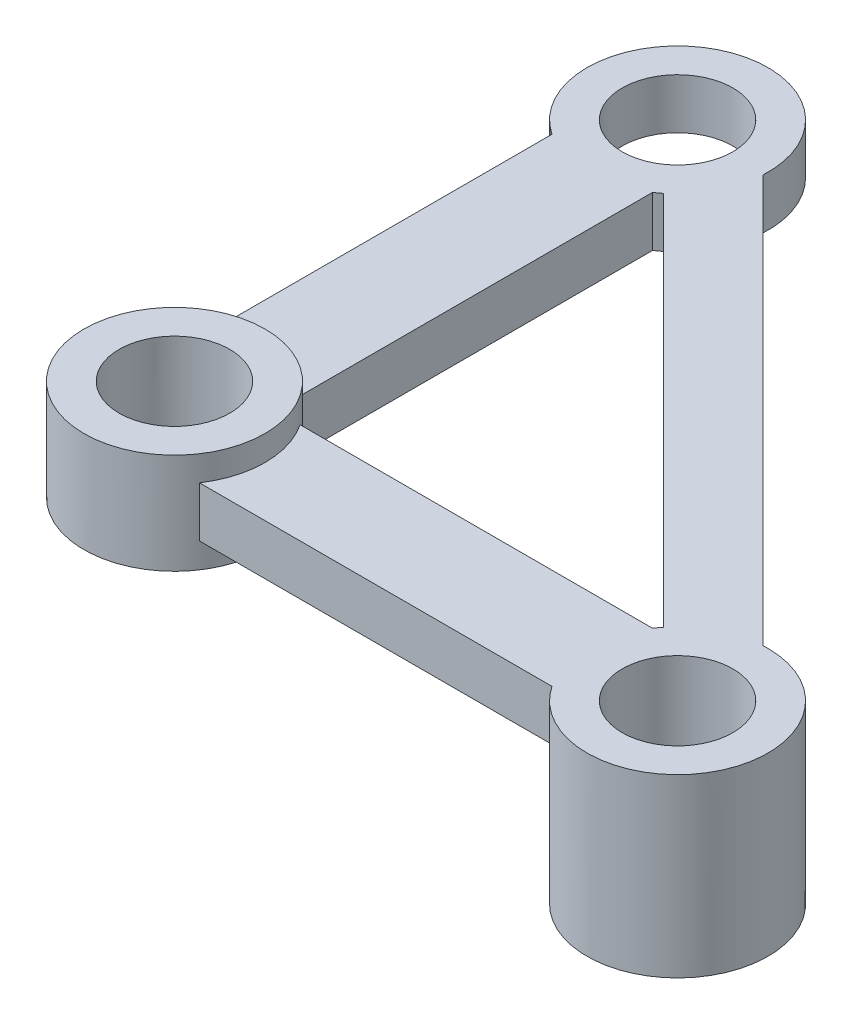
SolidWorks part; units mm, degrees
ref_plane "Front Plane" through (0, 0, 0) normal (0, 0, 1) x (1, 0, 0)
ref_plane "Top Plane" through (0, 0, 0) normal (0, 1, 0) x (1, 0, 0)
ref_plane "Right Plane" through (0, 0, 0) normal (1, 0, 0) x (0, 0, -1)
sketch "Sketch1" plane through (0, 0, 0) normal (0, 1, 0) x (1, 0, 0)
  line L0 (-5, -7.4833) -> (-5, -42.5167)
  line L1 (5, -7.4833) -> (5, -42.5167)
  line L2 (7.4833, -45) -> (42.5167, -45)
  line L3 (7.4833, -55) -> (42.5167, -55)
  line L4 (5.6174, -7.0317) -> (42.9683, -44.3826)
  line L5 (8.9861, -0.5008) -> (49.4992, -41.0139)
  arc A0 (5, -7.4833) -> (5.6174, -7.0317) centre (0, 0) ccw
  arc A1 (-5, -42.5167) -> (7.4833, -55) centre (0, -50) ccw
  arc A2 (42.5167, -55) -> (49.4992, -41.0139) centre (50, -50) ccw
  arc A3 (7.4833, -45) -> (5, -42.5167) centre (0, -50) ccw
  arc A4 (8.9861, -0.5008) -> (-5, -7.4833) centre (0, 0) ccw
  arc A5 (42.9683, -44.3826) -> (42.5167, -45) centre (50, -50) ccw
  dimension "D1" = 18
  dimension "D2" = 18
  dimension "D3" = 18
  dimension "D4" = 5
  dimension "D5" = 5
  dimension "D6" = 50
  dimension "D7" = 50
  dimension "D8" = 45
  dimension "D9" = 6
  dimension "D10" = 1
extrude "Boss-Extrude1" add sketch "Sketch1" along normal blind 5
sketch "Sketch6" plane through (0, 0, 0) normal (0, -1, 0) x (1, 0, 0)
  circle A0 centre (50, 50) radius 9
  dimension "D1" = 18
extrude "Boss-Extrude4" add sketch "Sketch6" along normal blind 12.5
sketch "Sketch2" plane through (0, 5, 0) normal (0, 1, 0) x (1, 0, 0)
  circle A0 centre (0, 0) radius 5.5
  dimension "D1" = 11
extrude "Cut-Extrude1" cut sketch "Sketch2" against normal blind 5
sketch "Sketch3" plane through (0, 0, 0) normal (0, -1, 0) x (1, 0, 0)
  circle A0 centre (0, 50) radius 9
  dimension "D1" = 18
extrude "Boss-Extrude2" add sketch "Sketch3" along normal blind 2.5
sketch "Sketch4" plane through (0, 5, 0) normal (0, 1, 0) x (1, 0, 0)
  circle A0 centre (0, -50) radius 9
  dimension "D1" = 18
extrude "Boss-Extrude3" add sketch "Sketch4" along normal blind 2.5
sketch "Sketch5" plane through (0, 7.5, 0) normal (0, 1, 0) x (1, 0, 0)
  circle A0 centre (0, -50) radius 5.5
  dimension "D1" = 11
extrude "Cut-Extrude2" cut sketch "Sketch5" against normal through all
sketch "Sketch7" plane through (0, 5, 0) normal (0, 1, 0) x (1, 0, 0)
  circle A0 centre (50, -50) radius 5.5
  dimension "D1" = 11
extrude "Cut-Extrude3" cut sketch "Sketch7" against normal through all
